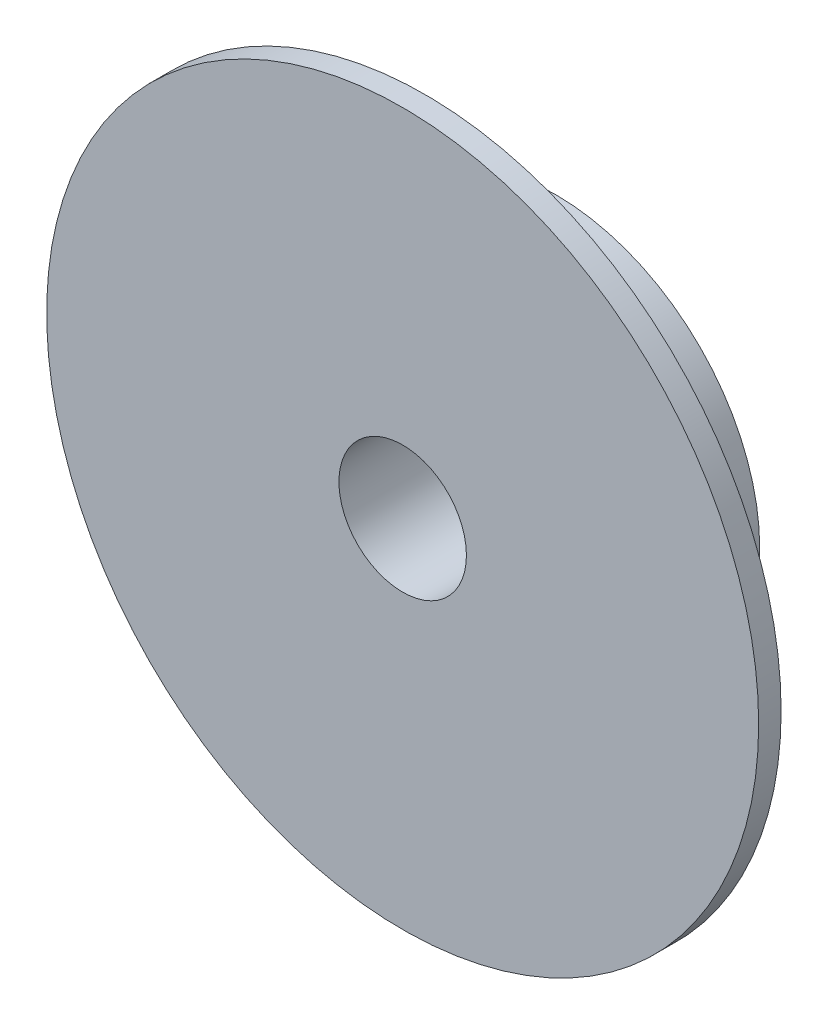
SolidWorks part; units mm, degrees
material "Alloy Steel"
ref_plane "Front Plane" through (0, 0, 0) normal (0, 0, 1) x (1, 0, 0)
ref_plane "Top Plane" through (0, 0, 0) normal (0, 1, 0) x (1, 0, 0)
ref_plane "Right Plane" through (0, 0, 0) normal (1, 0, 0) x (0, 0, -1)
sketch "Sketch1" plane through (0, 0, 0) normal (0, 0, 1) x (1, 0, 0)
  circle A0 centre (0, 0) radius 44.323
  dimension "OD" = 88.646
extrude "Boss-Extrude1" add sketch "Sketch1" along normal blind 2.794
sketch "Sketch2" plane through (0, 0, 0) normal (0, 0, -1) x (-1, 0, 0)
  circle A0 centre (0, 0) radius 25.4
  dimension "HubDia" = 50.8
extrude "Boss-Extrude2" add sketch "Sketch2" along normal blind 16.256
sketch "Sketch3" plane through (0, 0, 2.794) normal (0, 0, 1) x (1, 0, 0)
  circle A0 centre (0, 0) radius 7.9375
  dimension "Bore" = 15.875
extrude "Cut-Extrude1" cut sketch "Sketch3" against normal through all
